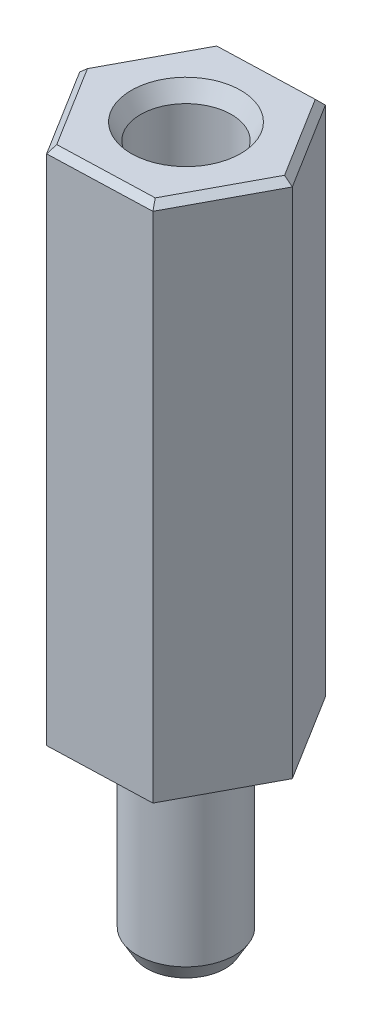
SolidWorks part; units mm, degrees
ref_plane "Front Plane" through (0, 0, 0) normal (0, 0, 1) x (1, 0, 0)
ref_plane "Top Plane" through (0, 0, 0) normal (0, 1, 0) x (1, 0, 0)
ref_plane "Right Plane" through (0, 0, 0) normal (1, 0, 0) x (0, 0, -1)
sketch "Sketch1" plane through (0, 0, 0) normal (0, 1, 0) x (1, 0, 0)
  line L1 (1.4975, 2.8002) -> (-1.6763, 2.6969)
  line L2 (-1.6763, 2.6969) -> (-3.1737, -0.1032)
  line L3 (-3.1737, -0.1032) -> (-1.4975, -2.8002)
  line L4 (-1.4975, -2.8002) -> (1.6763, -2.6969)
  line L5 (1.6763, -2.6969) -> (3.1737, 0.1032)
  line L6 (3.1737, 0.1032) -> (1.4975, 2.8002)
  circle A0 centre (0, 0) radius 2.75 construction
  dimension "D1" = 5.5
extrude "Boss-Extrude1" add sketch "Sketch1" along normal blind 16
sketch "Sketch2" plane through (0, 16, 0) normal (0, 1, 0) x (1, 0, 0)
  circle A0 centre (0, 0) radius 1.4
  dimension "D1" = 2.8
extrude "Cut-Extrude1" cut sketch "Sketch2" against normal blind 10
sketch "Sketch3" plane through (0, 0, 0) normal (0, -1, 0) x (1, 0, 0)
  circle A0 centre (0, 0) radius 1.5
  dimension "D1" = 3
extrude "Boss-Extrude2" add sketch "Sketch3" along normal blind 6
chamfer "Chamfer1" distance 0.5 angle 30 2 edges at (0, 16, 1.4) (0, -6, -1.5)
chamfer "Chamfer2" distance 0.2 angle 45 6 edges at (2.3356, 16, -1.4517) (-0.0894, 16, -2.7485) (-2.425, 16, -1.2969) (-2.3356, 16, 1.4517) (0.0894, 16, 2.7485) (2.425, 16, 1.2969)
